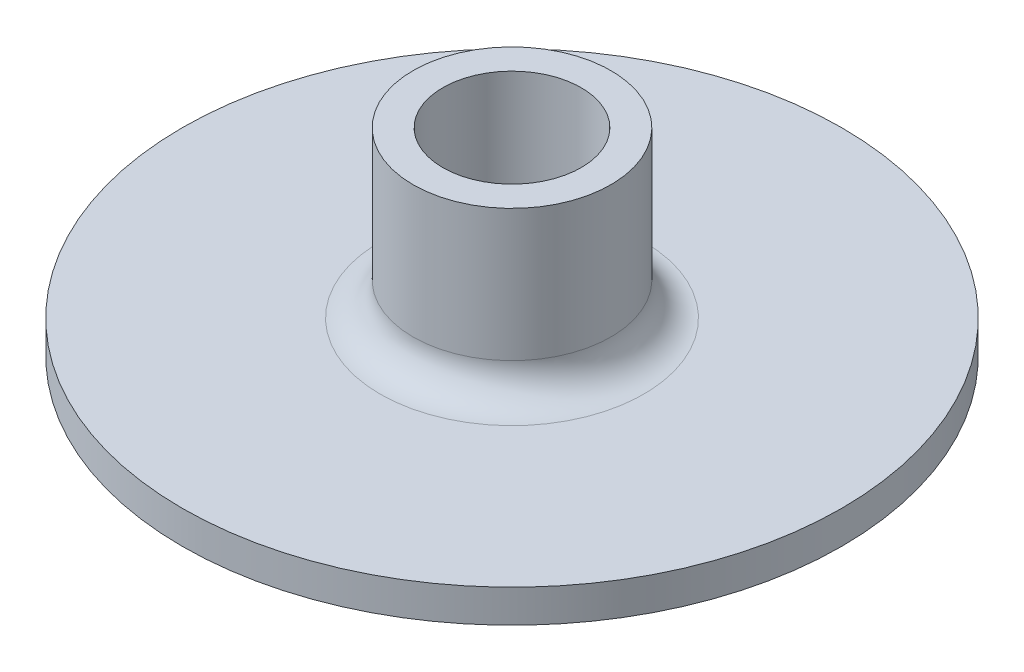
SolidWorks part; units mm, degrees
ref_plane "Спереди" through (0, 0, 0) normal (0, 0, 1) x (1, 0, 0)
ref_plane "Сверху" through (0, 0, 0) normal (0, 1, 0) x (1, 0, 0)
ref_plane "Справа" through (0, 0, 0) normal (1, 0, 0) x (0, 0, -1)
sketch "Эскиз1" plane through (0, 0, 0) normal (0, 1, 0) x (1, 0, 0)
  circle A0 centre (0, 0) radius 10.5
  circle A1 centre (0, 0) radius 50
extrude "Вытянуть1" add sketch "Эскиз1" along normal blind 30
sketch "Эскиз2" plane through (0, 30, 0) normal (0, 1, 0) x (1, 0, 0)
  circle A0 centre (0, 0) radius 15
  circle A1 centre (0, 0) radius 54.5114
extrude "Вытянуть2" cut sketch "Эскиз2" against normal blind 25
sketch "Эскиз3" plane through (0, 0, 0) normal (0, -1, 0) x (1, 0, 0)
  circle A0 centre (0, 0) radius 28
  circle A1 centre (0, 0) radius 19
  circle A2 centre (0, 25) radius 1.5
  circle A3 centre (25, 0) radius 1.5
  circle A4 centre (0, -25) radius 1.5
  circle A5 centre (-25, 0) radius 1.5
extrude "Вытянуть3" add sketch "Эскиз3" along normal blind 9
sketch "Эскиз4" plane through (0, -9, 0) normal (0, -1, 0) x (1, 0, 0)
  circle A0 centre (0, 0) radius 22.1
extrude "Вытянуть4" cut sketch "Эскиз4" against normal blind 3
fillet "Скругление3" radius 5 1 edges at (0, 5, 15)
